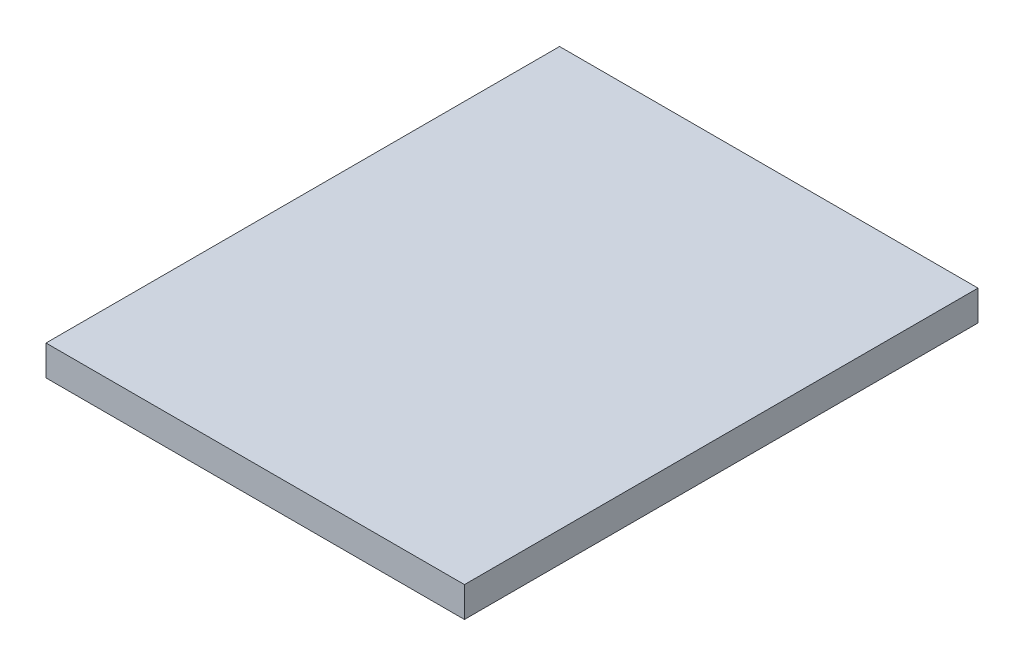
SolidWorks part; units mm, degrees
ref_plane "CL Y" through (0, 0, 0) normal (0, 0, 1) x (1, 0, 0)
ref_plane "Bottom" through (0, 0, 0) normal (0, 1, 0) x (1, 0, 0)
ref_plane "CL X" through (0, 0, 0) normal (1, 0, 0) x (0, 0, -1)
sketch "Sketch1" plane through (0, 0, 0) normal (0, 1, 0) x (1, 0, 0)
  line L0 (0, -50) -> (0, 50) construction
  line L1 (-22, 27) -> (22, 27)
  line L2 (-22, 27) -> (-22, -27)
  line L3 (-22, -27) -> (22, -27)
  line L4 (22, 27) -> (22, -27)
  line L5 (-50, 0) -> (50, 0) construction
  point P4 (0, 27)
  point P7 (22, 0)
  dimension "D1" = 44
  dimension "D2" = 54
extrude "Boss-Extrude1" add sketch "Sketch1" along normal blind 3.18
